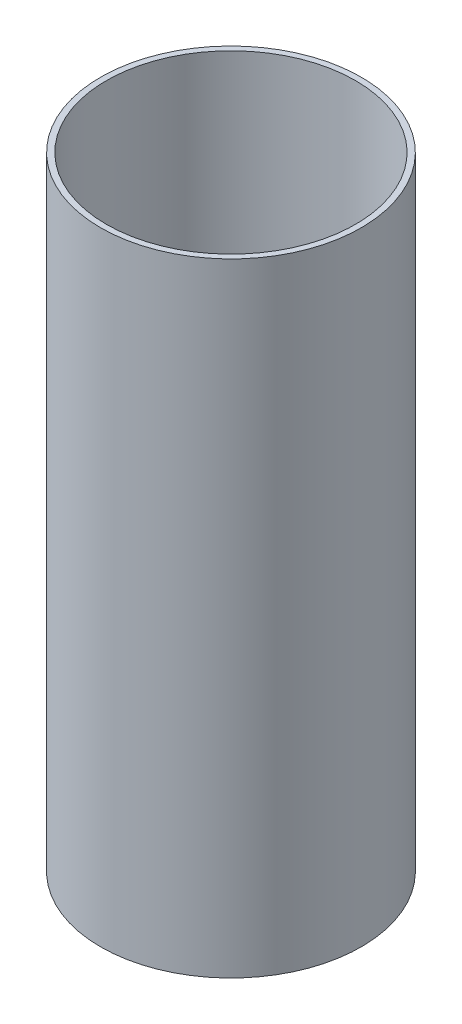
SolidWorks part; units mm, degrees
ref_plane "Front Plane" through (0, 0, 0) normal (0, 0, 1) x (1, 0, 0)
ref_plane "Top Plane" through (0, 0, 0) normal (0, 1, 0) x (1, 0, 0)
ref_plane "Right Plane" through (0, 0, 0) normal (1, 0, 0) x (0, 0, -1)
sketch "Sketch1" plane through (0, 0, 0) normal (0, 1, 0) x (1, 0, 0)
  circle A0 centre (0, 0) radius 16.75
  circle A1 centre (0, 0) radius 16
  dimension "D1" = 33.5
  dimension "D2" = 32
extrude "Boss-Extrude1" add sketch "Sketch1" along normal blind 80
